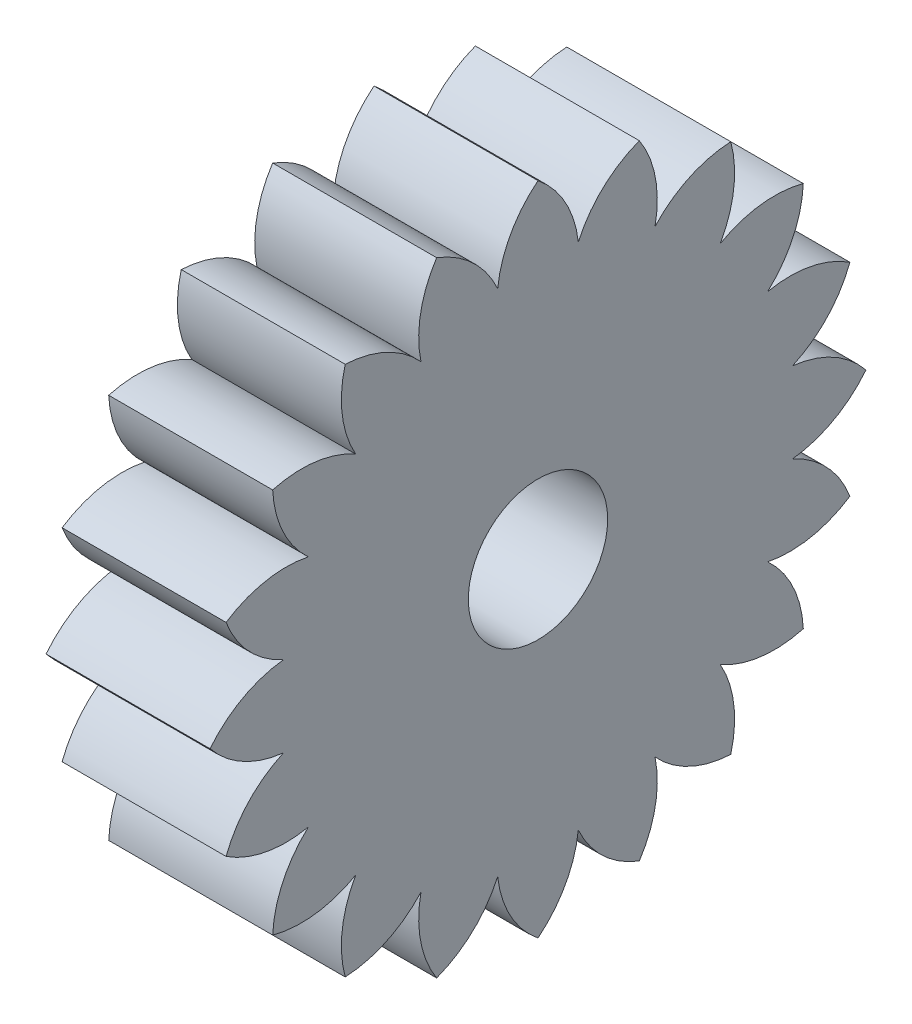
SolidWorks part; units mm, degrees
ref_plane "정면" through (0, 0, 0) normal (0, 0, 1) x (1, 0, 0)
ref_plane "윗면" through (0, 0, 0) normal (0, 1, 0) x (1, 0, 0)
ref_plane "우측면" through (0, 0, 0) normal (1, 0, 0) x (0, 0, -1)
sketch "스케치1" plane through (0, 0, 0) normal (1, 0, 0) x (0, 0, -1)
  line L0 (0, 0) -> (46.5062, 0) construction
  line L1 (0, 0) -> (0, 34.6154) construction
  line L2 (0, 0) -> (0, 12) construction
  line L3 (1.5, 0) -> (1.5, 8.8741) construction
  circle A1 centre (0, 0) radius 9 construction
  arc A2 (0, 12) -> (1.5, 8.8741) centre (-2.507, 8.8741) cw
  arc A3 (0, 12) -> (-1.5, 8.8741) centre (2.507, 8.8741) ccw
  arc A4 (-1.5, 8.8741) -> (1.5, 8.8741) centre (0, 0) ccw
  dimension "D1" = 9
  dimension "D2" = 12
  dimension "D3" = 1.5
extrude "보스-돌출1" add sketch "스케치1" along normal offset from surface (6 mm away) 1
pattern_circular "원형 패턴1" count 20 over 360 about axis through (0, 0, 0) along (1, 0, 0) of "보스-돌출1"
sketch "스케치2" plane through (6, 0, 0) normal (1, 0, 0) x (0, 0, -1)
  circle A0 centre (0, 0) radius 2.25 construction
  circle A2 centre (0, 0) radius 2.25 construction
  circle A3 centre (0, 0) radius 2.55
  dimension "D1" = 0.3
extrude "컷-돌출1" cut sketch "스케치2" against normal through all
